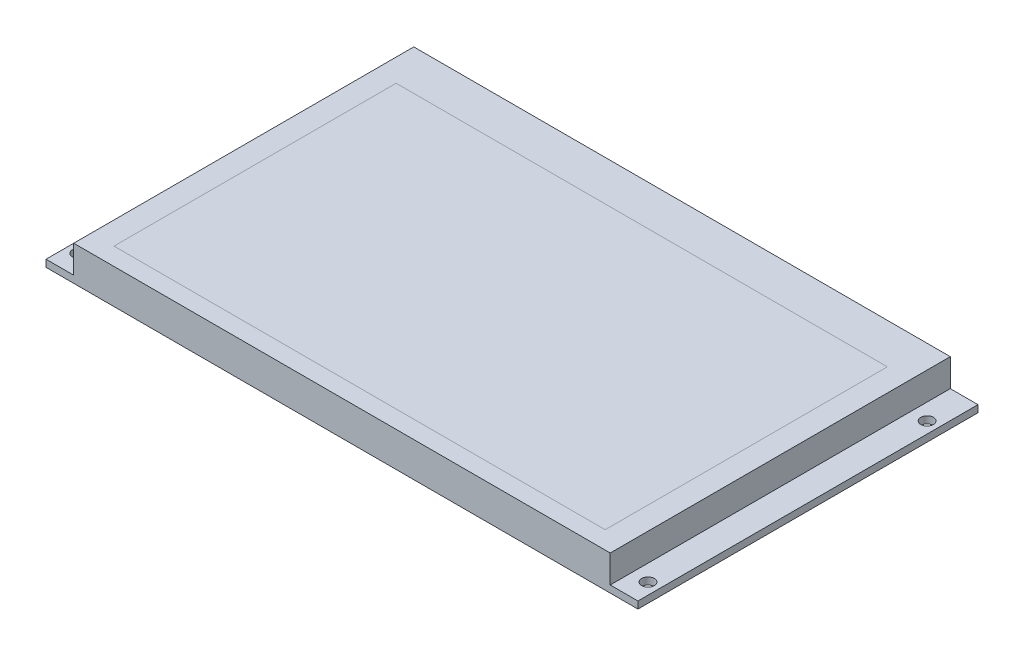
SolidWorks part; units mm, degrees
ref_plane "前视基准面" through (0, 0, 0) normal (0, 0, 1) x (1, 0, 0)
ref_plane "上视基准面" through (0, 0, 0) normal (0, 1, 0) x (1, 0, 0)
ref_plane "右视基准面" through (0, 0, 0) normal (1, 0, 0) x (0, 0, -1)
other "Configuration Table"
sketch "草图1" plane through (0, 0, 0) normal (0, 1, 0) x (1, 0, 0)
  line L1 (-58.75, -33.75) -> (58.75, -33.75)
  line L2 (-58.75, -33.75) -> (-58.75, 33.75)
  line L3 (-58.75, 33.75) -> (58.75, 33.75)
  line L4 (58.75, -33.75) -> (58.75, 33.75)
  line L5 (-58.75, -33.75) -> (58.75, 33.75) construction
  line L6 (-58.75, 33.75) -> (58.75, -33.75) construction
  point P0 (0, 0)
  dimension "D1" = 117.5
  dimension "D2" = 67.5
extrude "凸台-拉伸1" add sketch "草图1" along normal blind 1.4
sketch "草图2" plane through (0, 1.4, 0) normal (0, 1, 0) x (1, 0, 0)
  line L0 (58.75, 33.75) -> (-58.75, 33.75) construction
  line L1 (-53.25, 33.75) -> (53.25, 33.75)
  line L2 (-53.25, 33.75) -> (-53.25, -33.75)
  line L3 (-53.25, -33.75) -> (53.25, -33.75)
  line L4 (53.25, 33.75) -> (53.25, -33.75)
  line L5 (-58.75, -33.75) -> (58.75, -33.75) construction
  line L6 (-58.75, 33.75) -> (-58.75, -33.75) construction
  line L7 (58.75, -33.75) -> (58.75, 33.75) construction
  dimension "D1" = 5.5
  dimension "D2" = 5.5
extrude "凸台-拉伸2" add sketch "草图2" along normal blind 5.5
sketch "草图3" plane through (0, 6.9, 0) normal (0, 1, 0) x (1, 0, 0)
  line L0 (53.25, -33.75) -> (53.25, 33.75) construction
  line L1 (-48.75, 25.75) -> (48.75, 25.75)
  line L2 (-48.75, 25.75) -> (-48.75, -30.25)
  line L3 (-48.75, -30.25) -> (48.75, -30.25)
  line L4 (48.75, 25.75) -> (48.75, -30.25)
  line L5 (-53.25, 33.75) -> (-53.25, -33.75) construction
  line L6 (-53.25, -33.75) -> (53.25, -33.75) construction
  line L7 (53.25, 33.75) -> (-53.25, 33.75) construction
  dimension "D1" = 4.5
  dimension "D2" = 4.5
  dimension "D3" = 3.5
  dimension "D4" = 8
split line "分割线1"
sketch "草图5" plane through (0, 1.4, 0) normal (0, 1, 0) x (1, 0, 0)
  line L0 (-53.25, 33.75) -> (-58.75, 33.75) construction
  line L1 (-58.75, 33.75) -> (-58.75, -33.75) construction
  line L2 (-58.75, -33.75) -> (-53.25, -33.75) construction
  line L4 (58.75, -33.75) -> (58.75, 33.75) construction
  circle A0 centre (-56.5, -29.5) radius 1.25
  circle A1 centre (-56.5, 25.9) radius 1.25
  circle A2 centre (56.5, 25.9) radius 1.25
  circle A3 centre (56.5, -29.5) radius 1.25
  dimension "D1" = 2.5
  dimension "D2" = 7.85
  dimension "D3" = 2.25
  dimension "D4" = 4.25
  dimension "D6" = 2.25
extrude "切除-拉伸1" cut sketch "草图5" against normal up to next
sketch "草图6" plane through (0, 0, 0) normal (0, -1, 0) x (1, 0, 0)
  line L0 (58.75, 33.75) -> (58.75, -33.75) construction
  line L1 (-4.75, 30.25) -> (25.25, 30.25)
  line L2 (-4.75, 30.25) -> (-4.75, 24.25)
  line L3 (-4.75, 24.25) -> (25.25, 24.25)
  line L4 (25.25, 30.25) -> (25.25, 24.25)
  line L5 (-58.75, 33.75) -> (58.75, 33.75) construction
  dimension "D1" = 33.5
  dimension "D2" = 30
  dimension "D3" = 6
  dimension "D4" = 3.5
extrude "凸台-拉伸3" add sketch "草图6" along normal blind 2
sketch "草图7" plane through (0, -2, 0) normal (0, -1, 0) x (1, 0, 0)
  line L0 (-3.25, 30.25) -> (-3.25, 27.75)
  line L2 (-3.25, 27.75) -> (23.75, 27.75)
  line L3 (23.75, 27.75) -> (23.75, 30.25)
  line L4 (25.25, 30.25) -> (-4.75, 30.25) construction
  line L5 (23.75, 30.25) -> (-3.25, 30.25)
  line L6 (25.25, 24.25) -> (25.25, 30.25) construction
  line L8 (-4.75, 30.25) -> (-4.75, 24.25) construction
  line L9 (-4.75, 24.25) -> (25.25, 24.25) construction
  dimension "D1" = 1.5
  dimension "D2" = 1.5
  dimension "D3" = 3.5
split line "分割线2"
